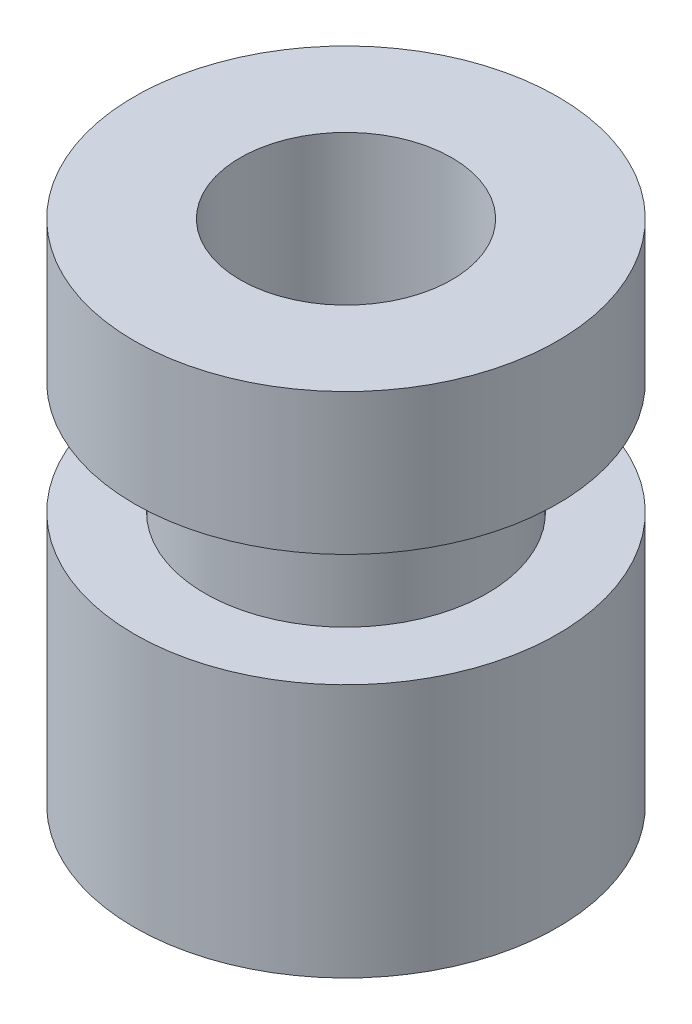
SolidWorks part; units mm, degrees
material "ABS"
ref_plane "Front Plane" through (0, 0, 0) normal (0, 0, 1) x (1, 0, 0)
ref_plane "Top Plane" through (0, 0, 0) normal (0, 1, 0) x (1, 0, 0)
ref_plane "Right Plane" through (0, 0, 0) normal (1, 0, 0) x (0, 0, -1)
sketch "Sketch1" plane through (0, 0, 0) normal (0, 0, 1) x (1, 0, 0)
  line L0 (0, 0) -> (0, 9.1) construction
  line L1 (1.5, 7.2) -> (3, 7.2)
  line L2 (3, 7.2) -> (3, 5.2)
  line L3 (3, 5.2) -> (2, 5.2)
  line L4 (2, 5.2) -> (2, 3.6)
  line L5 (2, 3.6) -> (3, 3.6)
  line L6 (3, 3.6) -> (3, 0)
  line L7 (3, 0) -> (1.5, 0)
  line L8 (1.5, 7.2) -> (1.5, 0)
  dimension "D1" = 3
  dimension "D2" = 7.2
  dimension "D3" = 1.6
  dimension "D4" = 2
  dimension "D5" = 4
  dimension "D6" = 3
revolve "Revolve1" add sketch "Sketch1" angle 360 about L0
